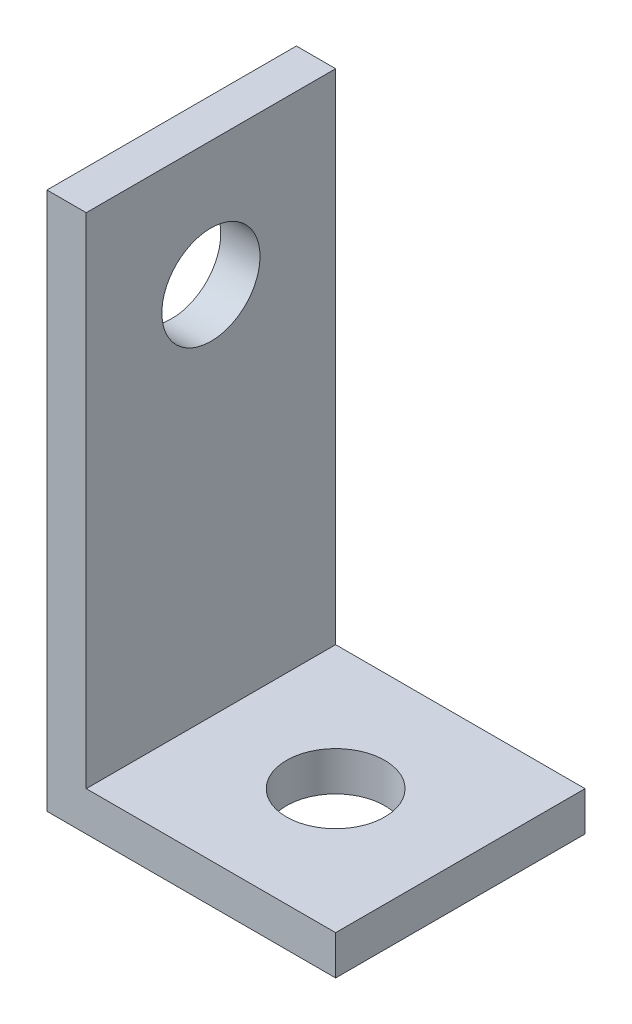
SolidWorks part; units mm, degrees
ref_plane "Front Plane" through (0, 0, 0) normal (0, 0, 1) x (1, 0, 0)
ref_plane "Top Plane" through (0, 0, 0) normal (0, 1, 0) x (1, 0, 0)
ref_plane "Right Plane" through (0, 0, 0) normal (1, 0, 0) x (0, 0, -1)
sketch "Sketch1" plane through (0, 0, 0) normal (0, 0, 1) x (1, 0, 0)
  line L1 (0, 0) -> (14.7, 0)
  line L2 (0, 0) -> (0, 2)
  line L3 (0, 2) -> (14.7, 2)
  line L4 (14.7, 0) -> (14.7, 2)
  line L5 (0, 2) -> (2, 2)
  line L6 (0, 2) -> (0, 27.4)
  line L7 (0, 27.4) -> (2, 27.4)
  line L8 (2, 2) -> (2, 27.4)
  dimension "D1" = 2
  dimension "D2" = 12.7
  dimension "D3" = 25.4
extrude "Boss-Extrude1" add sketch "Sketch1" along normal blind 12.7 contours L1 L4 L3 L2 | L6 L5 L8 L7
hole_wizard "Ø5.0mm Dowel Hole1" positions "Sketch2" profile "Sketch3" hole size "Ø5.0" standard "ANSI Metric" end condition through all
sketch "Sketch2" plane through (2, 0, 0) normal (1, 0, 0) x (0, 0, -1)
  line L0 (-12.7, 27.4) -> (0, 27.4) construction
  point P0 (-6.35, 21.05)
  point P5 (-6.35, 27.4)
  dimension "D1" = 6.35
sketch "Sketch3" plane through (2, 21.05, 6.35) normal (0, 1, 0) x (0, 0, -1)
  line L0 (0, 0) -> (0, 2)
  line L1 (0, 2) -> (2.5, 2)
  line L2 (2.5, 2) -> (2.5, 0)
  line L5 (2.5, 0) -> (0, 0)
  line L11 (0, -6.35) -> (0, 107.95) construction
  dimension "Thru Hole Dia." = 5
  dimension "Thru Hole Depth" = 2
hole_wizard "Ø5.0mm Dowel Hole2" positions "Sketch4" profile "Sketch5" hole size "Ø5.0" standard "ANSI Metric" end condition through all
sketch "Sketch4" plane through (0, 2, 0) normal (0, 1, 0) x (1, 0, 0)
  line L0 (2, -12.7) -> (14.7, -12.7) construction
  line L1 (14.7, -12.7) -> (14.7, 0) construction
  point P0 (8.35, -6.35)
  point P5 (8.35, -12.7)
  point P8 (14.7, -6.35)
sketch "Sketch5" plane through (8.35, 2, 6.35) normal (1, 0, 0) x (0, 0, 1)
  line L0 (0, 0) -> (0, 2)
  line L1 (0, 2) -> (2.5, 2)
  line L2 (2.5, 2) -> (2.5, 0)
  line L5 (2.5, 0) -> (0, 0)
  line L11 (0, -6.35) -> (0, 107.95) construction
  dimension "Thru Hole Dia." = 5
  dimension "Thru Hole Depth" = 2
